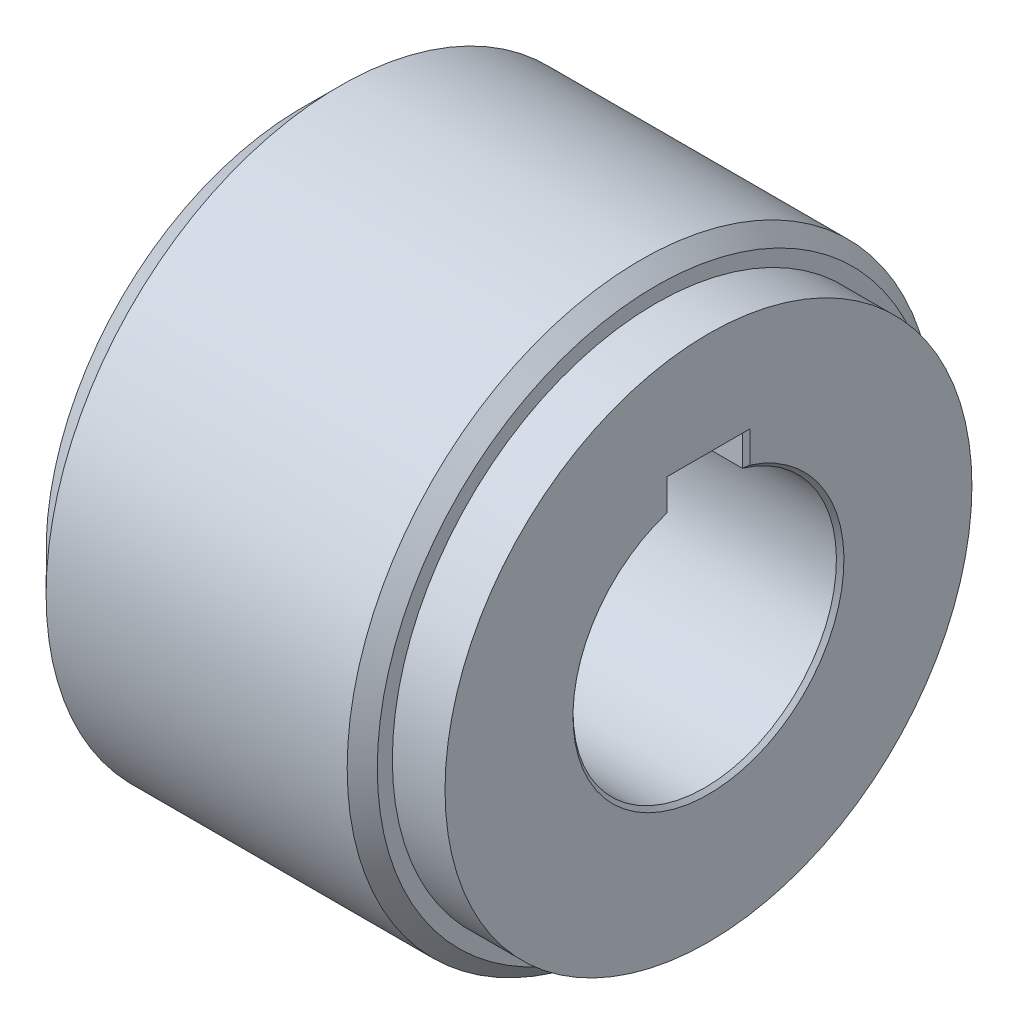
SolidWorks part; units mm, degrees
material "AISI 304"
ref_plane "Спереди" through (0, 0, 0) normal (0, 0, 1) x (1, 0, 0)
ref_plane "Сверху" through (0, 0, 0) normal (0, 1, 0) x (1, 0, 0)
ref_plane "Справа" through (0, 0, 0) normal (1, 0, 0) x (0, 0, -1)
other "Configuration Table"
sketch "Эскиз1" plane through (0, 0, 0) normal (1, 0, 0) x (0, 0, -1)
  line L0 (0, 0) -> (0, 20.8) construction
  line L1 (-5, 20.8) -> (5, 20.8)
  line L2 (5, 20.8) -> (5, 16.7705)
  line L3 (-5, 20.8) -> (-5, 16.7705)
  arc A0 (-5, 16.7705) -> (5, 16.7705) centre (0, 0) ccw
  circle A1 centre (0, 0) radius 39
  point P8 (0, 20.8)
  dimension "D1" = 35
  dimension "D4" = 78
  dimension "D2" = 10
  dimension "D3" = 38.3
extrude "Бобышка-Вытянуть1" add sketch "Эскиз1" along normal mid plane 54
chamfer "Фаска1" distance 5 angle 45 1 edges at (-27, 0, -39)
chamfer "Фаска2" distance 0.5 angle 45 8 edges at (27, 18.7853, -5) (27, 20.8, 0) (27, 18.7853, 5) (27, -17.5, 0) (-27, 18.7853, 5) (-27, 20.8, 0) (-27, 18.7853, -5) (-27, -17.5, 0)
sketch "Эскиз3" plane through (0, 0, 0) normal (0, 0, 1) x (1, 0, 0)
  line L0 (0, 0) -> (27, 0) construction
  line L1 (27, -39) -> (27, 39) construction
  line L2 (27, 35) -> (20, 35)
  line L3 (20, 35) -> (20, 37)
  line L4 (20, 37) -> (18, 39)
  line L5 (27, 39) -> (-22, 39) construction
  line L6 (18, 39) -> (27, 39)
  line L7 (27, 39) -> (27, 35)
  dimension "D1" = 70
  dimension "D2" = 78
  dimension "D3" = 45
  dimension "D4" = 2
  dimension "D5" = 7
  dimension "D6" = 2
revolve "Вырез-Повернуть1" cut sketch "Эскиз3" angle 360 about L0
